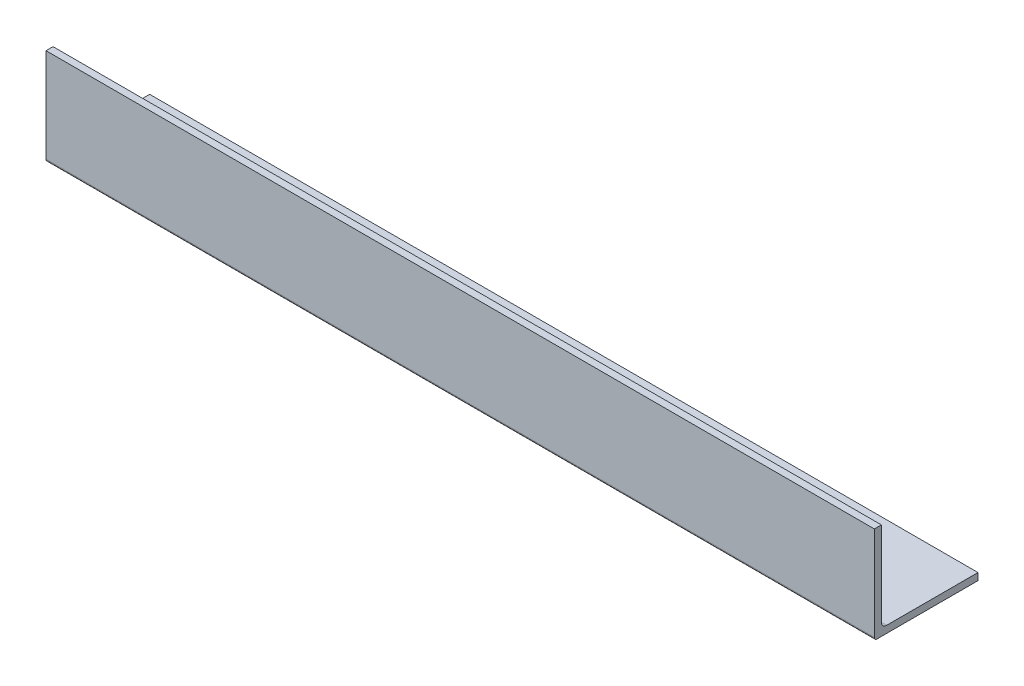
SolidWorks part; units mm, degrees
ref_plane "Alzado" through (0, 0, 0) normal (0, 0, 1) x (1, 0, 0)
ref_plane "Planta" through (0, 0, 0) normal (0, 1, 0) x (1, 0, 0)
ref_plane "Vista lateral" through (0, 0, 0) normal (1, 0, 0) x (0, 0, -1)
sketch "Croquis1" plane through (0, 0, 0) normal (0, 0, 1) x (1, 0, 0)
  line L0 (235.625, 27.5) -> (-235.625, -27.5) construction
  line L1 (-235.625, 27.5) -> (235.625, 27.5)
  line L2 (-235.625, 27.5) -> (-235.625, -27.5)
  line L3 (-235.625, -27.5) -> (235.625, -27.5)
  line L4 (235.625, 27.5) -> (235.625, -27.5)
  dimension "D1" = 471.25
  dimension "D2" = 55
extrude "Saliente-Extruir1" add sketch "Croquis1" along normal blind 4
sketch "Croquis2" plane through (0, 0, 0) normal (0, 0, -1) x (-1, 0, 0)
  line L0 (-235.625, -27.5) -> (-235.625, 27.5) construction
  line L1 (-235.625, -23.5) -> (235.625, -23.5)
  line L2 (-235.625, -23.5) -> (-235.625, -27.5)
  line L3 (-235.625, -27.5) -> (235.625, -27.5)
  line L4 (235.625, -23.5) -> (235.625, -27.5)
  dimension "D1" = 4
extrude "Saliente-Extruir2" add sketch "Croquis2" along normal blind 55
fillet "Redondeo1" radius 3 1 edges
fillet "Redondeo2" radius 1.5 1 edges at (0, -27.5, 4)
